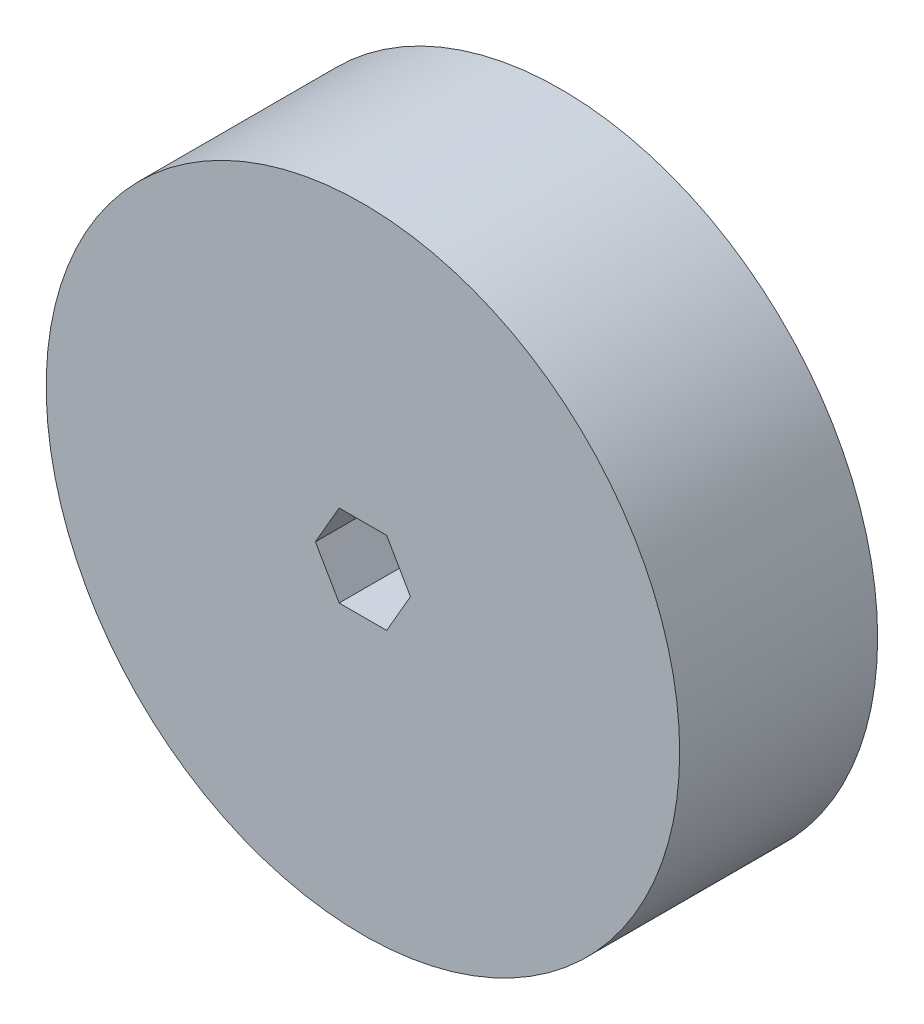
SolidWorks part; units mm, degrees
ref_plane "Front Plane" through (0, 0, 0) normal (0, 0, 1) x (1, 0, 0)
ref_plane "Top Plane" through (0, 0, 0) normal (0, 1, 0) x (1, 0, 0)
ref_plane "Right Plane" through (0, 0, 0) normal (1, 0, 0) x (0, 0, -1)
sketch "Sketch1" plane through (0, 0, 0) normal (0, 0, 1) x (1, 0, 0)
  circle A0 centre (0, 0) radius 24
  dimension "D1" = 48
extrude "Boss-Extrude1" add sketch "Sketch1" along normal blind 15
sketch "Sketch2" plane through (0, 0, 15) normal (0, 0, 1) x (1, 0, 0)
  line L1 (3.6, 0) -> (1.8, 3.1177)
  line L2 (1.8, 3.1177) -> (-1.8, 3.1177)
  line L3 (-1.8, 3.1177) -> (-3.6, 0)
  line L4 (-3.6, 0) -> (-1.8, -3.1177)
  line L5 (-1.8, -3.1177) -> (1.8, -3.1177)
  line L6 (1.8, -3.1177) -> (3.6, 0)
  circle A0 centre (0, 0) radius 3.1177 construction
  dimension "D1" = 3.6
extrude "Cut-Extrude1" cut sketch "Sketch2" against normal through all
scale "Scale1" scale about centroid uniform scaling yes scale factor 0.75
